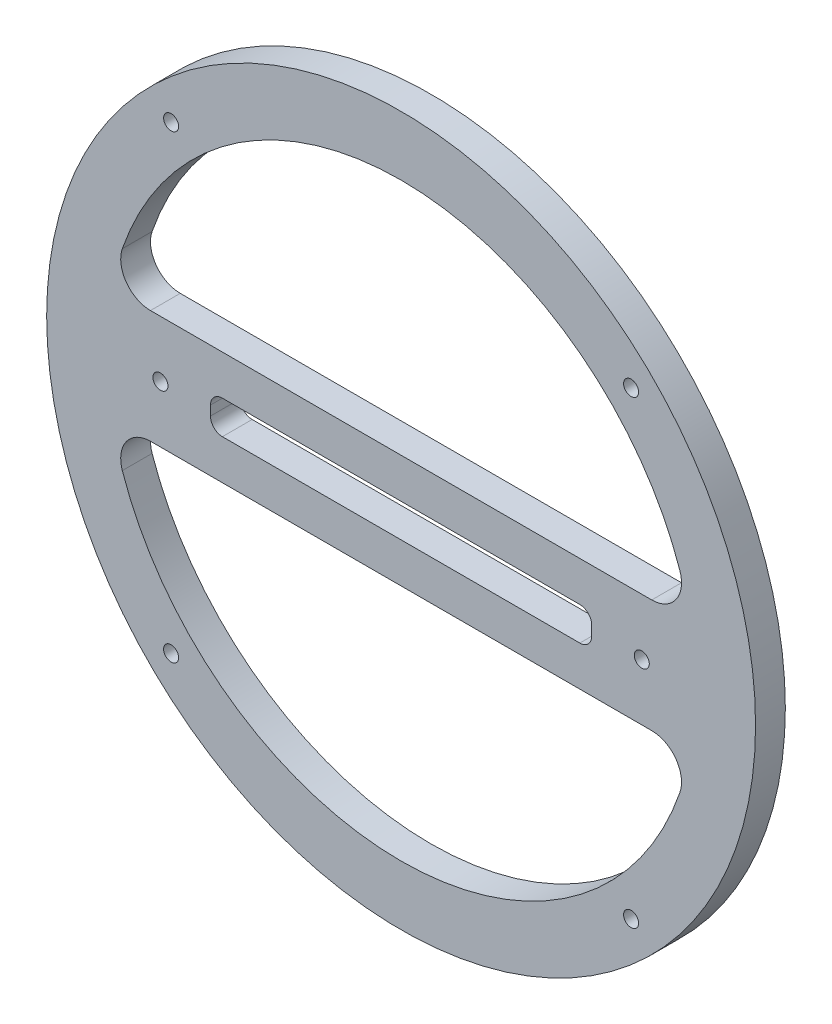
SolidWorks part; units mm, degrees
ref_plane "Front Plane" through (0, 0, 0) normal (0, 0, 1) x (1, 0, 0)
ref_plane "Top Plane" through (0, 0, 0) normal (0, 1, 0) x (1, 0, 0)
ref_plane "Right Plane" through (0, 0, 0) normal (1, 0, 0) x (0, 0, -1)
sketch "Sketch1" plane through (0, 0, 0) normal (0, 0, 1) x (1, 0, 0)
  line L0 (-101.6586, 0) -> (110.617, 0) construction
  line L1 (-53.4306, 12.065) -> (53.4306, 12.065)
  line L2 (-53.4306, -12.065) -> (53.4306, -12.065)
  line L3 (0, 93.8435) -> (0, -155.6241) construction
  line L4 (-38.1, -3.556) -> (38.1, -3.556)
  line L5 (-40.64, -1.016) -> (-40.64, 1.016)
  line L6 (-38.1, 3.556) -> (38.1, 3.556)
  line L7 (40.64, -1.016) -> (40.64, 1.016)
  line L8 (-40.64, -3.556) -> (40.64, 3.556) construction
  line L9 (-40.64, 3.556) -> (40.64, -3.556) construction
  circle A0 centre (0, 0) radius 75.565
  arc A1 (59.4341, 20.4841) -> (-59.4341, 20.4841) centre (0, 0) ccw
  arc A2 (-59.4341, -20.4841) -> (59.4341, -20.4841) centre (0, 0) ccw
  arc A3 (-53.4306, -12.065) -> (-59.4341, -20.4841) centre (-53.4306, -18.415) ccw
  arc A4 (53.4306, -12.065) -> (59.4341, -20.4841) centre (53.4306, -18.415) cw
  arc A5 (53.4306, 12.065) -> (59.4341, 20.4841) centre (53.4306, 18.415) ccw
  arc A6 (-53.4306, 12.065) -> (-59.4341, 20.4841) centre (-53.4306, 18.415) cw
  arc A7 (38.1, -3.556) -> (40.64, -1.016) centre (38.1, -1.016) ccw
  arc A8 (38.1, 3.556) -> (40.64, 1.016) centre (38.1, 1.016) cw
  arc A9 (-38.1, -3.556) -> (-40.64, -1.016) centre (-38.1, -1.016) cw
  arc A10 (-40.64, 1.016) -> (-38.1, 3.556) centre (-38.1, 1.016) cw
  circle A11 centre (-51.308, 0) radius 1.6
  circle A12 centre (51.308, 0) radius 1.6
  circle A13 centre (49.0322, 49.0322) radius 1.6
  circle A17 centre (49.0322, -49.0322) radius 1.6
  circle A18 centre (-49.0322, -49.0322) radius 1.6
  circle A19 centre (-49.0322, 49.0322) radius 1.6
  point P11 (-61.6964, -12.065)
  point P14 (61.6964, -12.065)
  point P17 (61.6964, 12.065)
  point P20 (-61.6964, 12.065)
  dimension "D1" = 151.13
  dimension "D2" = 125.73
  dimension "D4" = 6.35
  dimension "D7" = 2.54
  dimension "D8" = 3.2
  dimension "D13" = 3.2
  dimension "D3" = 12.065
  dimension "D5" = 7.112
  dimension "D6" = 81.28
  dimension "D9" = 51.308
  dimension "D10" = 49.0322
  dimension "D11" = 49.0322
  dimension "D12" = 4
extrude "Boss-Extrude1" add sketch "Sketch1" against normal blind 6.35
